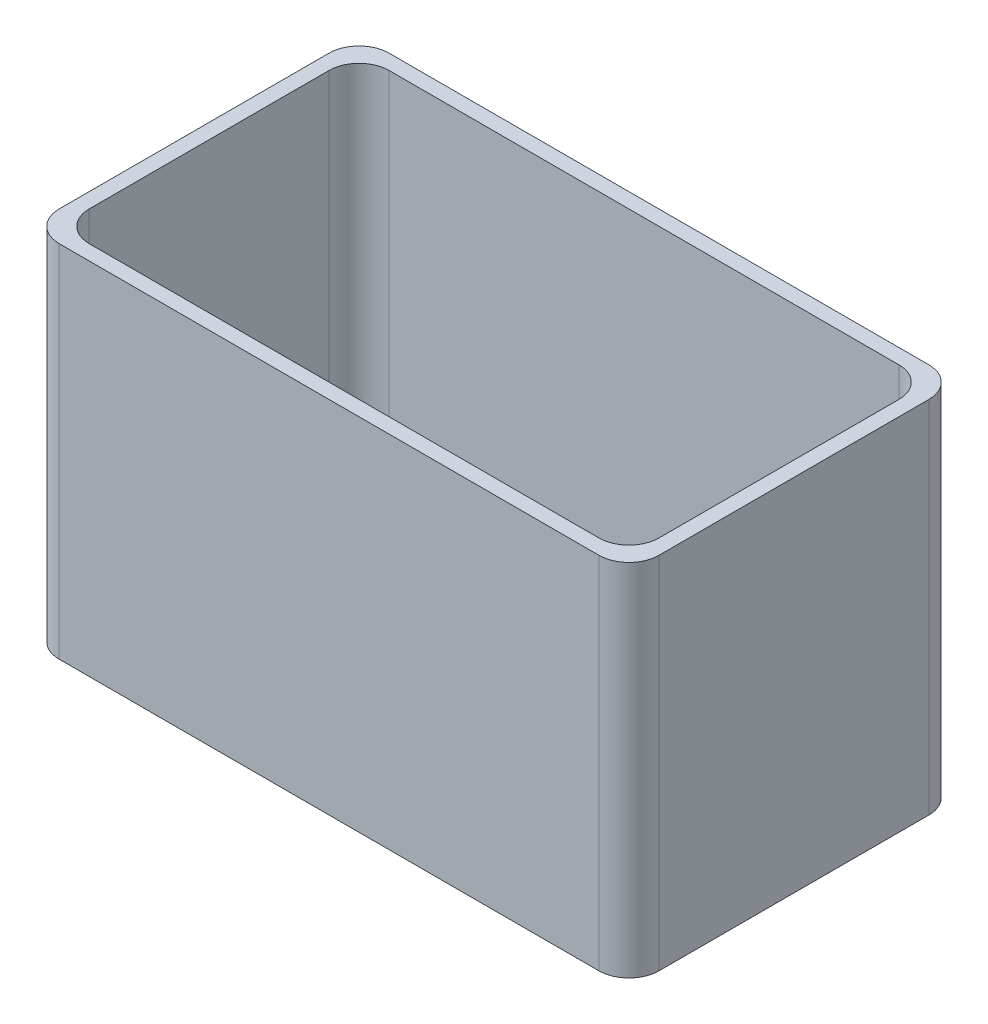
SolidWorks part; units mm, degrees
ref_plane "Front Plane" through (0, 0, 0) normal (0, 0, 1) x (1, 0, 0)
ref_plane "Top Plane" through (0, 0, 0) normal (0, 1, 0) x (1, 0, 0)
ref_plane "Right Plane" through (0, 0, 0) normal (1, 0, 0) x (0, 0, -1)
sketch "Sketch1" plane through (0, 0, 0) normal (0, 1, 0) x (1, 0, 0)
  line L1 (0, 0) -> (200, 0)
  line L2 (0, 0) -> (0, 110)
  line L3 (0, 110) -> (200, 110)
  line L4 (200, 0) -> (200, 110)
  dimension "D1" = 110
  dimension "D2" = 200
extrude "Boss-Extrude1" add sketch "Sketch1" along normal blind 6
sketch "Sketch2" plane through (0, 6, 0) normal (0, 1, 0) x (1, 0, 0)
  line L0 (5, 5) -> (5, 105)
  line L1 (0, 0) -> (200, 0)
  line L2 (0, 0) -> (0, 110)
  line L3 (0, 110) -> (200, 110)
  line L4 (200, 0) -> (200, 110)
  line L5 (5, 105) -> (195, 105)
  line L6 (195, 5) -> (195, 105)
  line L7 (5, 5) -> (195, 5)
  dimension "D1" = 5
extrude "Boss-Extrude2" add sketch "Sketch2" along normal blind 114
sketch "Sketch3" plane through (0, 6, 0) normal (0, 1, 0) x (1, 0, 0)
  line L1 (45, 65) -> (155, 65)
  line L2 (45, 65) -> (45, 45)
  line L3 (45, 45) -> (155, 45)
  line L4 (155, 65) -> (155, 45)
  line L5 (0, 110) -> (0, 0) construction
  line L6 (0, 55) -> (45, 55) construction
  line L7 (100, 65) -> (100, 110) construction
  line L8 (200, 110) -> (0, 110) construction
  line L9 (195, 105) -> (5, 105) construction
  line L10 (195, 5) -> (195, 105) construction
  dimension "D1" = 40
  dimension "D2" = 40
extrude "Cut-Extrude1" cut sketch "Sketch3" against normal through all
sketch "Sketch4" plane through (0, 6, 0) normal (0, 1, 0) x (1, 0, 0)
  line L0 (40, 70) -> (40, 40)
  line L1 (45, 65) -> (155, 65)
  line L2 (45, 65) -> (45, 45)
  line L3 (45, 45) -> (155, 45)
  line L4 (155, 65) -> (155, 45)
  line L5 (40, 40) -> (160, 40)
  line L6 (160, 70) -> (160, 40)
  line L7 (40, 70) -> (160, 70)
  dimension "D1" = 5
extrude "Boss-Extrude3" add sketch "Sketch4" along normal blind 15
chamfer "Chamfer2" distance 3 angle 45 4 edges at (155, 0, -55) (100, 0, -65) (45, 0, -55) (100, 0, -45)
fillet "Fillet1" radius 10 12 edges at (0, 60, 0) (0, 60, -110) (200, 60, -110) (200, 60, 0) (195, 6, -55) (195, 63, -5) (195, 63, -105) (5, 63, -105) (5, 63, -5) (100, 6, -5) (100, 6, -105) (5, 6, -55)
fillet "Fillet2" radius 4 12 edges at (40, 6, -55) (100, 6, -40) (100, 6, -70) (155, 12, -45) (155, 12, -65) (45, 12, -45) (45, 12, -65) (40, 13.5, -40) (40, 13.5, -70) (160, 13.5, -40) (160, 13.5, -70) (160, 6, -55)
